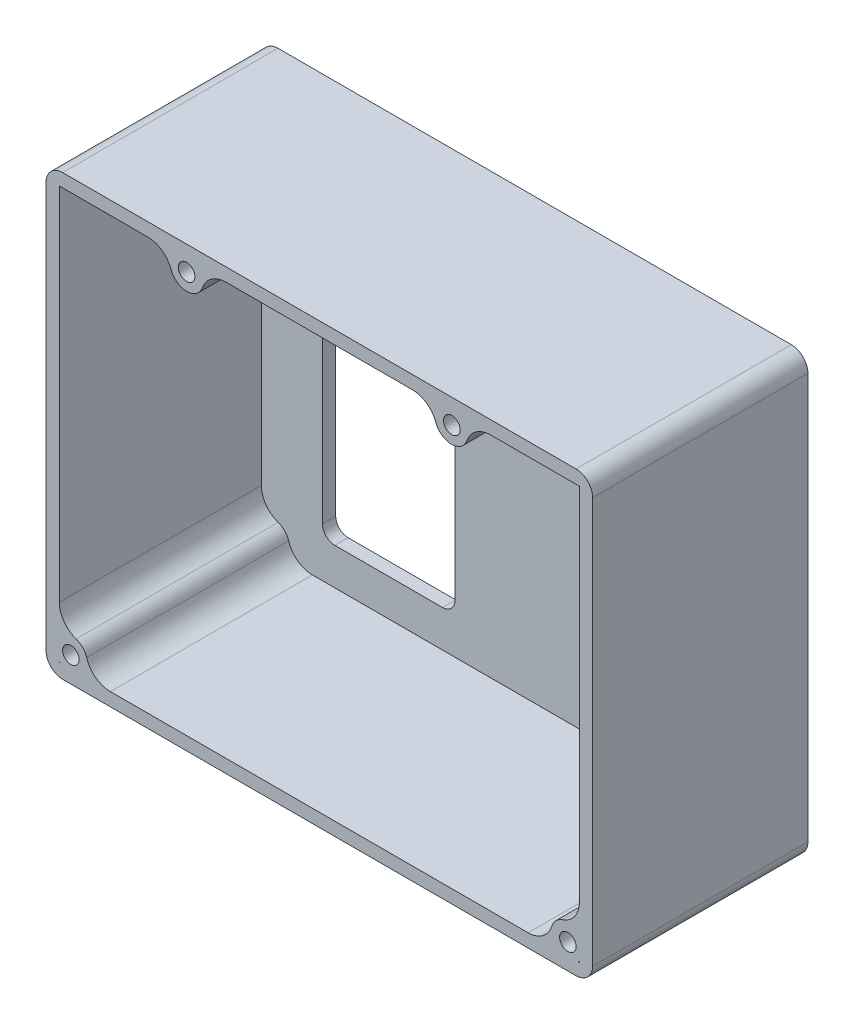
SolidWorks part; units mm, degrees
ref_plane "Front Plane" through (0, 0, 0) normal (0, 0, 1) x (1, 0, 0)
ref_plane "Top Plane" through (0, 0, 0) normal (0, 1, 0) x (1, 0, 0)
ref_plane "Right Plane" through (0, 0, 0) normal (1, 0, 0) x (0, 0, -1)
other "Graphic1"
ref_plane "Plane1" through (0, 0, 40) normal (0, 0, 1) x (1, 0, 0)
sketch "Sketch1" plane through (0, 0, 40) normal (0, 0, 1) x (1, 0, 0)
  line L1 (73.0043, 494.9484) -> (139.0043, 494.9484)
  line L2 (73.0043, 494.9484) -> (73.0043, 441.9484)
  line L3 (73.0043, 441.9484) -> (139.0043, 441.9484)
  line L4 (139.0043, 494.9484) -> (139.0043, 441.9484)
  dimension "D1" = 66
  dimension "D2" = 53
extrude "Boss-Extrude1" add sketch "Sketch1" along normal blind 26
shell "Shell1" thickness 1.6
fillet "Fillet1" radius 2 4 edges at (73.0043, 494.9484, 53) (73.0043, 441.9484, 53) (139.0043, 441.9484, 53) (139.0043, 494.9484, 53)
sketch "Sketch2" plane through (0, 0, 41.6) normal (0, 0, 1) x (1, 0, 0)
  line L0 (113.9809, 447.9976) -> (129.9809, 447.9976)
  line L1 (81.9809, 475.9976) -> (97.9809, 475.9976)
  line L2 (81.9809, 475.9976) -> (81.9809, 447.9976)
  line L3 (81.9809, 447.9976) -> (97.9809, 447.9976)
  line L4 (97.9809, 475.9976) -> (97.9809, 447.9976)
  line L5 (113.9809, 475.9976) -> (113.9809, 447.9976)
  line L6 (113.9809, 475.9976) -> (129.9809, 475.9976)
  line L7 (129.9809, 475.9976) -> (129.9809, 447.9976)
  circle A0 centre (79.9322, 485.0919) radius 2.5
  circle A1 centre (132.1215, 485.0919) radius 2.5
  dimension "D1" = 16
  dimension "D2" = 28
extrude "Cut-Extrude1" cut sketch "Sketch2" against normal blind 5
sketch "Sketch3" plane through (0, 0, 41.6) normal (0, 0, 1) x (1, 0, 0)
  circle A0 centre (89.9976, 492.0139) radius 2
  circle A1 centre (121.955, 492.0139) radius 2
  circle A2 centre (75.9853, 445.0906) radius 2
  circle A3 centre (135.9971, 445.0906) radius 2
extrude "Boss-Extrude2" add sketch "Sketch3" along normal up to surface (24.4 mm away) up to face at (106.0043, 468.4484, 66)
fillet "Fillet2" radius 3 8 edges at (77.2587, 443.5484, 53.8) (74.6043, 446.5373, 53.8) (134.7237, 443.5484, 53.8) (137.4043, 446.5119, 53.8) (88.508, 493.3484, 53.8) (91.4872, 493.3484, 53.8) (120.4653, 493.3484, 53.8) (123.4446, 493.3484, 53.8)
fillet "Fillet3" radius 1.5 8 edges at (129.9809, 447.9976, 40.8) (97.9809, 447.9976, 40.8) (113.9809, 447.9976, 40.8) (81.9809, 447.9976, 40.8) (97.9809, 475.9976, 40.8) (81.9809, 475.9976, 40.8) (113.9809, 475.9976, 40.8) (129.9809, 475.9976, 40.8)
sketch "Sketch4" plane through (0, 0, 66) normal (0, 0, 1) x (1, 0, 0)
  circle A0 centre (89.9751, 492.0437) radius 1
  circle A1 centre (122.0056, 492.0437) radius 1
  circle A2 centre (75.9942, 444.9943) radius 1
  circle A3 centre (136.0207, 444.9943) radius 1
  point P2 (75.9942, 444.9943)
  point P9 (136.0207, 444.9943)
extrude "Cut-Extrude2" cut sketch "Sketch4" against normal through all
